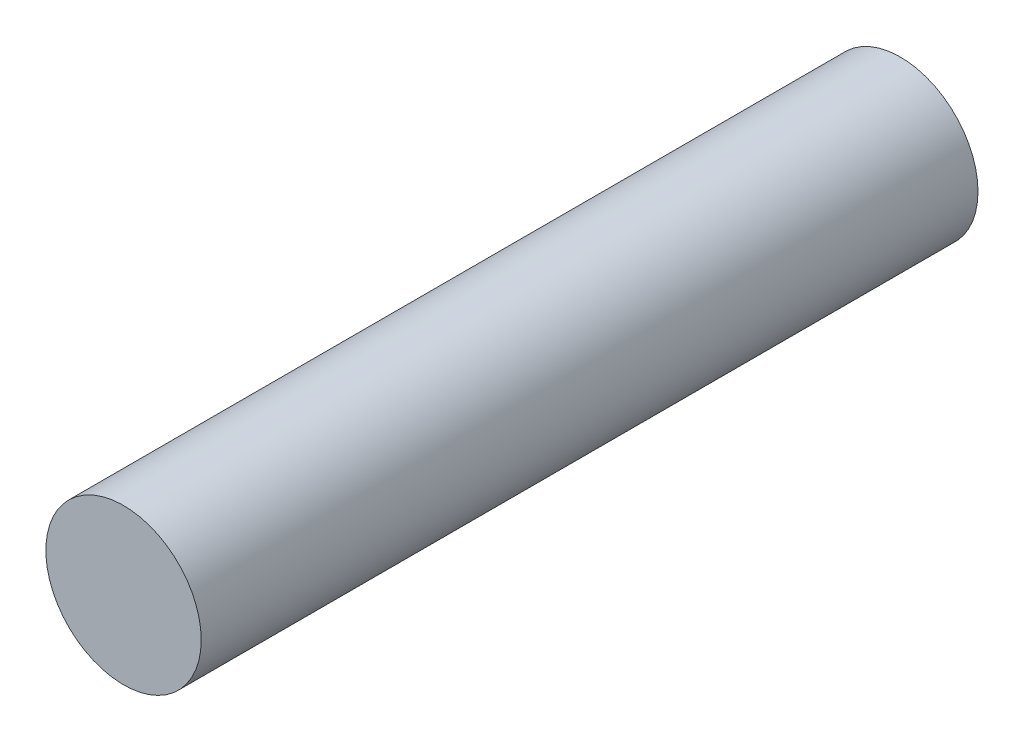
SolidWorks part; units mm, degrees
ref_plane "Ön Düzlem" through (0, 0, 0) normal (0, 0, 1) x (1, 0, 0)
ref_plane "Üst Düzlem" through (0, 0, 0) normal (0, 1, 0) x (1, 0, 0)
ref_plane "Sağ Düzlem" through (0, 0, 0) normal (1, 0, 0) x (0, 0, -1)
sketch "Sketch1" plane through (0, 0, 0) normal (0, 0, 1) x (1, 0, 0)
  circle A0 centre (0, 0) radius 5
  dimension "D1" = 10
extrude "Boss-Extrude1" add sketch "Sketch1" along normal blind 50
